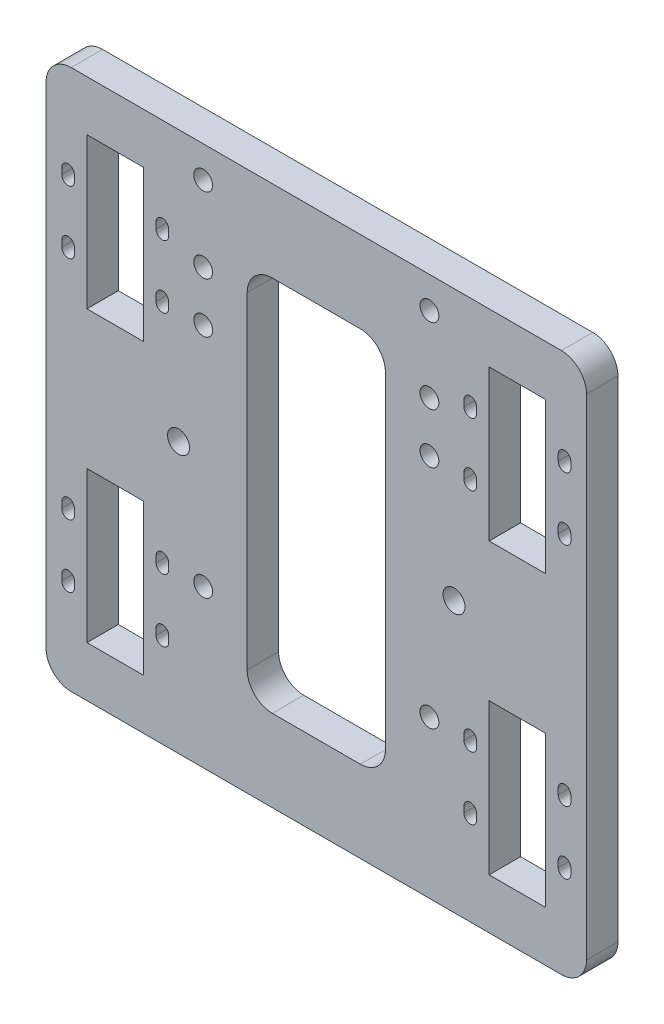
SolidWorks part; units mm, degrees
material "Maple"
ref_plane "Front Plane" through (0, 0, 0) normal (0, 0, 1) x (1, 0, 0)
ref_plane "Top Plane" through (0, 0, 0) normal (0, 1, 0) x (1, 0, 0)
ref_plane "Right Plane" through (0, 0, 0) normal (1, 0, 0) x (0, 0, -1)
sketch "Sketch1" plane through (0, 0, 0) normal (0, 0, 1) x (1, 0, 0)
  line L0 (67.5, 61.5) -> (67.5, 60.5) construction
  line L1 (0, 86) -> (86, 86)
  line L2 (0, 86) -> (0, 0)
  line L3 (0, 0) -> (86, 0)
  line L4 (86, 86) -> (86, 0)
  line L5 (70.5, 78) -> (79.5, 78)
  line L6 (70.5, 78) -> (70.5, 54)
  line L7 (70.5, 54) -> (79.5, 54) construction
  line L8 (79.5, 78) -> (79.5, 54)
  line L9 (68.5, 61.5) -> (68.5, 60.5)
  line L10 (66.5, 61.5) -> (66.5, 60.5)
  line L11 (75, 78) -> (75, 54) construction
  line L12 (67.5, 61) -> (75, 61) construction
  line L13 (82.5, 61.5) -> (82.5, 60.5) construction
  line L14 (81.5, 61.5) -> (81.5, 60.5)
  line L15 (83.5, 61.5) -> (83.5, 60.5)
  line L16 (70.5, 54) -> (79.5, 54)
  line L17 (67.5, 24.5) -> (67.5, 25.5) construction
  line L18 (68.5, 24.5) -> (68.5, 25.5)
  line L19 (66.5, 24.5) -> (66.5, 25.5)
  line L20 (82.5, 24.5) -> (82.5, 25.5) construction
  line L21 (81.5, 24.5) -> (81.5, 25.5)
  line L22 (83.5, 24.5) -> (83.5, 25.5)
  line L23 (67.5, 25) -> (75, 25) construction
  line L24 (75, 8) -> (75, 32) construction
  line L25 (70.5, 32) -> (79.5, 32) construction
  line L26 (70.5, 32) -> (79.5, 32)
  line L27 (79.5, 8) -> (79.5, 32)
  line L28 (70.5, 8) -> (70.5, 32)
  line L29 (70.5, 8) -> (79.5, 8)
  line L30 (18.5, 61.5) -> (18.5, 60.5) construction
  line L31 (17.5, 61.5) -> (17.5, 60.5)
  line L32 (19.5, 61.5) -> (19.5, 60.5)
  line L33 (3.5, 61.5) -> (3.5, 60.5) construction
  line L34 (4.5, 61.5) -> (4.5, 60.5)
  line L35 (2.5, 61.5) -> (2.5, 60.5)
  line L36 (18.5, 24.5) -> (18.5, 25.5) construction
  line L37 (17.5, 24.5) -> (17.5, 25.5)
  line L38 (19.5, 24.5) -> (19.5, 25.5)
  line L39 (3.5, 24.5) -> (3.5, 25.5) construction
  line L40 (4.5, 24.5) -> (4.5, 25.5)
  line L41 (2.5, 24.5) -> (2.5, 25.5)
  line L42 (15.5, 32) -> (6.5, 32) construction
  line L43 (11, 8) -> (11, 32) construction
  line L44 (18.5, 25) -> (11, 25) construction
  line L45 (18.5, 61) -> (11, 61) construction
  line L46 (11, 78) -> (11, 54) construction
  line L47 (15.5, 54) -> (6.5, 54) construction
  line L48 (15.5, 8) -> (6.5, 8)
  line L49 (15.5, 8) -> (15.5, 32)
  line L50 (6.5, 8) -> (6.5, 32)
  line L51 (15.5, 32) -> (6.5, 32)
  line L52 (15.5, 54) -> (6.5, 54)
  line L53 (6.5, 78) -> (6.5, 54)
  line L54 (15.5, 78) -> (15.5, 54)
  line L55 (15.5, 78) -> (6.5, 78)
  line L56 (43, 21.0797) -> (43, 0) construction
  line L57 (21.0797, 43) -> (0, 43) construction
  line L58 (32, 73) -> (54, 13) construction
  line L59 (32, 73) -> (54, 73)
  line L60 (32, 73) -> (32, 13)
  line L61 (32, 13) -> (54, 13)
  line L62 (54, 73) -> (54, 13)
  line L63 (61, 61) -> (25, 25) construction
  line L64 (25, 61) -> (61, 61) construction
  line L65 (25, 61) -> (25, 25) construction
  line L66 (25, 25) -> (61, 25) construction
  line L67 (61, 61) -> (61, 25) construction
  line L68 (5, 37) -> (5, 49) construction
  line L69 (0, 75) -> (86, 75) construction
  line L70 (79.5, 66) -> (70.5, 66) construction
  line L71 (67.5, 70.5) -> (67.5, 71.5) construction
  line L72 (68.5, 70.5) -> (68.5, 71.5)
  line L73 (66.5, 70.5) -> (66.5, 71.5)
  line L74 (82.5, 70.5) -> (82.5, 71.5) construction
  line L75 (81.5, 70.5) -> (81.5, 71.5)
  line L76 (83.5, 70.5) -> (83.5, 71.5)
  line L77 (18.5, 70.5) -> (18.5, 71.5) construction
  line L78 (17.5, 70.5) -> (17.5, 71.5)
  line L79 (19.5, 70.5) -> (19.5, 71.5)
  line L80 (3.5, 70.5) -> (3.5, 71.5) construction
  line L81 (4.5, 70.5) -> (4.5, 71.5)
  line L82 (2.5, 70.5) -> (2.5, 71.5)
  line L83 (3.5, 15.5) -> (3.5, 14.5) construction
  line L84 (4.5, 15.5) -> (4.5, 14.5)
  line L85 (2.5, 15.5) -> (2.5, 14.5)
  line L86 (18.5, 15.5) -> (18.5, 14.5) construction
  line L87 (17.5, 15.5) -> (17.5, 14.5)
  line L88 (19.5, 15.5) -> (19.5, 14.5)
  line L89 (67.5, 15.5) -> (67.5, 14.5) construction
  line L90 (68.5, 15.5) -> (68.5, 14.5)
  line L91 (66.5, 15.5) -> (66.5, 14.5)
  line L92 (43, 64.9203) -> (43, 21.0797) construction
  line L93 (43, 64.9203) -> (64.9203, 43) construction
  line L94 (43, 64.9203) -> (21.0797, 43) construction
  line L95 (21.0797, 43) -> (43, 21.0797) construction
  line L96 (64.9203, 43) -> (43, 21.0797) construction
  line L97 (82.5, 15.5) -> (82.5, 14.5) construction
  line L98 (81.5, 15.5) -> (81.5, 14.5)
  line L99 (43, 43) -> (54, 43) construction
  line L100 (83.5, 15.5) -> (83.5, 14.5)
  arc A0 (68.5, 61.5) -> (66.5, 61.5) centre (67.5, 61.5) ccw
  arc A1 (66.5, 60.5) -> (68.5, 60.5) centre (67.5, 60.5) ccw
  arc A2 (81.5, 61.5) -> (83.5, 61.5) centre (82.5, 61.5) cw
  arc A3 (83.5, 60.5) -> (81.5, 60.5) centre (82.5, 60.5) cw
  arc A4 (68.5, 24.5) -> (66.5, 24.5) centre (67.5, 24.5) cw
  arc A5 (66.5, 25.5) -> (68.5, 25.5) centre (67.5, 25.5) cw
  arc A6 (81.5, 24.5) -> (83.5, 24.5) centre (82.5, 24.5) ccw
  arc A7 (83.5, 25.5) -> (81.5, 25.5) centre (82.5, 25.5) ccw
  arc A8 (17.5, 61.5) -> (19.5, 61.5) centre (18.5, 61.5) cw
  arc A9 (19.5, 60.5) -> (17.5, 60.5) centre (18.5, 60.5) cw
  arc A10 (4.5, 61.5) -> (2.5, 61.5) centre (3.5, 61.5) ccw
  arc A11 (2.5, 60.5) -> (4.5, 60.5) centre (3.5, 60.5) ccw
  arc A12 (17.5, 24.5) -> (19.5, 24.5) centre (18.5, 24.5) ccw
  arc A13 (19.5, 25.5) -> (17.5, 25.5) centre (18.5, 25.5) ccw
  arc A14 (4.5, 24.5) -> (2.5, 24.5) centre (3.5, 24.5) cw
  arc A15 (2.5, 25.5) -> (4.5, 25.5) centre (3.5, 25.5) cw
  circle A16 centre (25, 61) radius 1.5
  circle A17 centre (61, 61) radius 1.5
  circle A18 centre (61, 25) radius 1.5
  circle A19 centre (25, 25) radius 1.5
  arc A20 (68.5, 70.5) -> (66.5, 70.5) centre (67.5, 70.5) cw
  arc A21 (66.5, 71.5) -> (68.5, 71.5) centre (67.5, 71.5) cw
  circle A22 centre (25, 81) radius 1.5
  circle A23 centre (25, 69) radius 1.5
  circle A24 centre (61, 69) radius 1.5
  circle A25 centre (61, 81) radius 1.5
  arc A26 (81.5, 70.5) -> (83.5, 70.5) centre (82.5, 70.5) ccw
  arc A27 (83.5, 71.5) -> (81.5, 71.5) centre (82.5, 71.5) ccw
  arc A28 (17.5, 70.5) -> (19.5, 70.5) centre (18.5, 70.5) ccw
  arc A29 (19.5, 71.5) -> (17.5, 71.5) centre (18.5, 71.5) ccw
  arc A30 (4.5, 70.5) -> (2.5, 70.5) centre (3.5, 70.5) cw
  arc A31 (2.5, 71.5) -> (4.5, 71.5) centre (3.5, 71.5) cw
  circle A32 centre (43, 43) radius 11.5 construction
  circle A33 centre (43, 64.9203) radius 1.75 construction
  circle A34 centre (64.9203, 43) radius 1.75
  circle A35 centre (43, 21.0797) radius 1.75 construction
  circle A36 centre (21.0797, 43) radius 1.75
  arc A37 (4.5, 15.5) -> (2.5, 15.5) centre (3.5, 15.5) ccw
  arc A38 (2.5, 14.5) -> (4.5, 14.5) centre (3.5, 14.5) ccw
  arc A39 (17.5, 15.5) -> (19.5, 15.5) centre (18.5, 15.5) cw
  arc A40 (19.5, 14.5) -> (17.5, 14.5) centre (18.5, 14.5) cw
  arc A41 (68.5, 15.5) -> (66.5, 15.5) centre (67.5, 15.5) ccw
  arc A42 (66.5, 14.5) -> (68.5, 14.5) centre (67.5, 14.5) ccw
  arc A43 (81.5, 15.5) -> (83.5, 15.5) centre (82.5, 15.5) cw
  arc A44 (83.5, 14.5) -> (81.5, 14.5) centre (82.5, 14.5) cw
  point P10 (67.5, 61)
  point P20 (82.5, 61)
  point P29 (67.5, 25)
  point P37 (82.5, 25)
  point P52 (18.5, 61)
  point P59 (3.5, 61)
  point P66 (18.5, 25)
  point P73 (3.5, 25)
  point P100 (43, 43)
  point P105 (43, 43)
  point P114 (5, 43)
  point P125 (67.5, 71)
  point P136 (82.5, 71)
  point P143 (18.5, 71)
  point P150 (3.5, 71)
  point P157 (3.5, 15)
  point P171 (18.5, 15)
  point P179 (67.5, 15)
  point P186 (82.5, 15)
  dimension "D17" = 3.5
  dimension "D18" = 23
  dimension "D20" = 6
  dimension "D21" = 5
  dimension "D12" = 3
  dimension "D16" = 11
  dimension "D2" = 1
  dimension "D3" = 9
  dimension "D4" = 24
  dimension "D5" = 2
  dimension "D6" = 7.5
  dimension "D7" = 8
  dimension "D8" = 22
  dimension "D9" = 60
  dimension "D10" = 36
  dimension "D11" = 32
  dimension "D13" = 12
  dimension "D14" = 11
  dimension "D15" = 5
  dimension "D19" = 31
extrude "Boss-Extrude1" add sketch "Sketch1" along normal blind 5
fillet "Fillet1" radius 4 8 edges at (86, 0, 2.5) (0, 0, 2.5) (0, 86, 2.5) (86, 86, 2.5) (32, 73, 2.5) (54, 73, 2.5) (54, 13, 2.5) (32, 13, 2.5)
